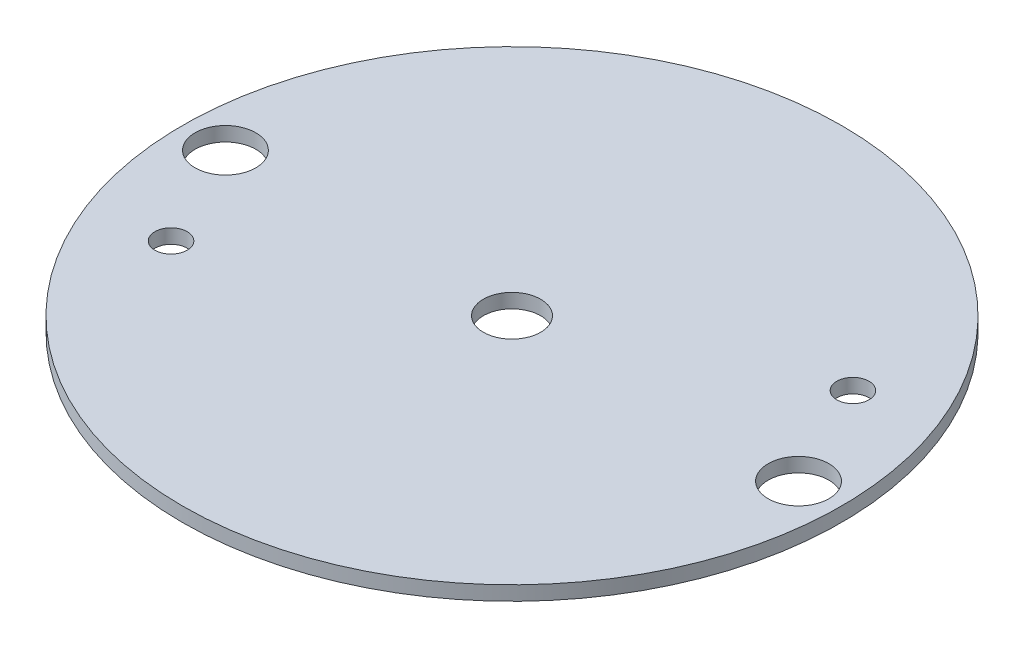
SolidWorks part; units mm, degrees
ref_plane "Front Plane" through (0, 0, 0) normal (0, 0, 1) x (1, 0, 0)
ref_plane "Top Plane" through (0, 0, 0) normal (0, 1, 0) x (1, 0, 0)
ref_plane "Right Plane" through (0, 0, 0) normal (1, 0, 0) x (0, 0, -1)
sketch "Sketch1" plane through (0, 0, 0) normal (0, 1, 0) x (1, 0, 0)
  circle A0 centre (0, 0) radius 73.0293
extrude "Boss-Extrude1" add sketch "Sketch1" along normal blind 3.175 contours A0
sketch "Sketch8" plane through (0, 3.175, 0) normal (0, 1, 0) x (1, 0, 0)
  circle A0 centre (0, 0) radius 6.35
extrude "Cut-Extrude3" cut sketch "Sketch8" against normal blind 16.256
sketch "Sketch10" plane through (0, 3.175, 0) normal (0, 1, 0) x (1, 0, 0)
  line L0 (63.5, 0) -> (-63.5, 0) construction
  circle A0 centre (-63.5, 0) radius 6.731
  circle A1 centre (63.5, 0) radius 6.731
  point P5 (0, 0)
extrude "Cut-Extrude4" cut sketch "Sketch10" against normal blind 25.4
sketch "Sketch11" plane through (0, 3.175, 0) normal (0, 1, 0) x (1, 0, 0)
  line L0 (52.1287, 23.4249) -> (-52.1287, -23.4249) construction
  circle A0 centre (-52.1287, -23.4249) radius 3.5719
  circle A1 centre (52.1287, 23.4249) radius 3.5719
  point P5 (0, 0)
extrude "Cut-Extrude5" cut sketch "Sketch11" against normal blind 254
